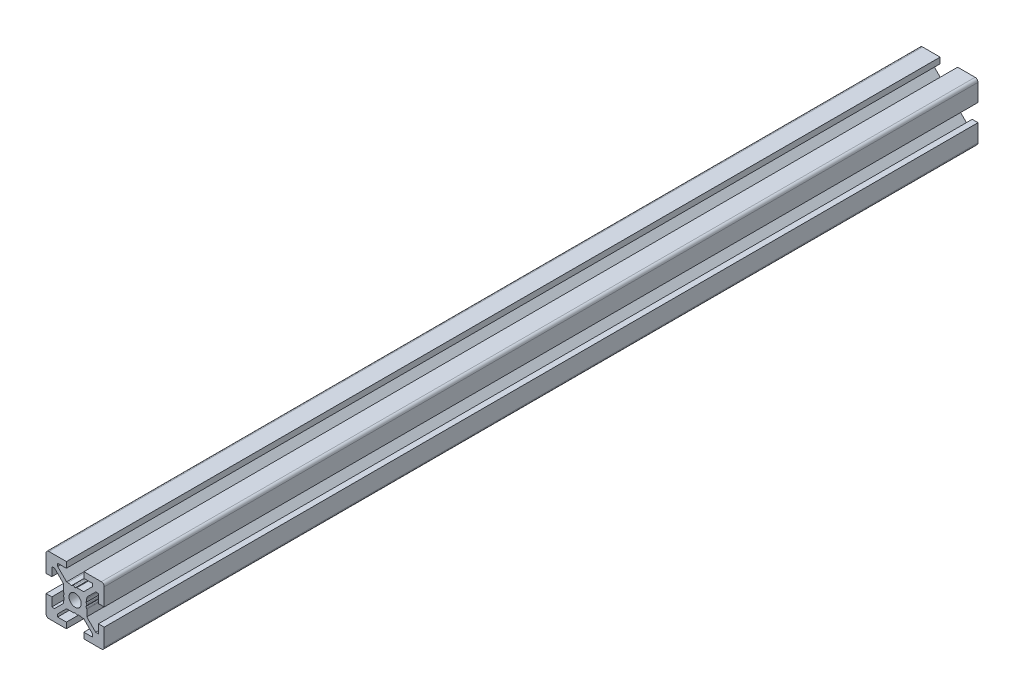
SolidWorks part; units mm, degrees
ref_plane "Front Plane" through (0, 0, 0) normal (0, 0, 1) x (1, 0, 0)
ref_plane "Top Plane" through (0, 0, 0) normal (0, 1, 0) x (1, 0, 0)
ref_plane "Right Plane" through (0, 0, 0) normal (1, 0, 0) x (0, 0, -1)
ref_plane "Plane1" through (0, 0, -2000) normal (0, 0, -1) x (-1, 0, 0)
sketch "Sketch1" plane through (0, 0, -2000) normal (0, 0, -1) x (-1, 0, 0)
  line L0 (10, -3) -> (8, -3)
  line L1 (8, -3) -> (8, -6)
  line L2 (8, -6) -> (7.0607, -6)
  line L3 (7.0607, -6) -> (4, -2.9393)
  line L4 (4, -2.9393) -> (4, -2.5)
  line L5 (4, -2.5) -> (3.751, -1.2189)
  line L6 (3.751, -1.2189) -> (3.933, -0.9036)
  line L7 (3.933, -0.4036) -> (3.7, 0)
  line L8 (3.7, 0) -> (3.933, 0.4036)
  line L9 (4, 0.6536) -> (4, 2.9393)
  line L10 (4, 2.9393) -> (7.0607, 6)
  line L11 (7.0607, 6) -> (8, 6)
  line L12 (8, 6) -> (8, 3)
  line L13 (8, 3) -> (10, 3)
  line L14 (10, 3) -> (10, 9)
  line L15 (9, 10) -> (3, 10)
  line L16 (3, 10) -> (3, 8)
  line L17 (3, 8) -> (6, 8)
  line L18 (6, 8) -> (6, 7.0607)
  line L19 (6, 7.0607) -> (2.9393, 4)
  line L20 (2.9393, 4) -> (2.5, 4)
  line L21 (2.5, 4) -> (1.2189, 3.751)
  line L22 (1.2189, 3.751) -> (0.9036, 3.933)
  line L23 (0.4036, 3.933) -> (0, 3.7)
  line L24 (0, 3.7) -> (-0.4036, 3.933)
  line L25 (-0.6536, 4) -> (-2.9393, 4)
  line L26 (-2.9393, 4) -> (-6, 7.0607)
  line L27 (-6, 7.0607) -> (-6, 8)
  line L28 (-6, 8) -> (-3, 8)
  line L29 (-3, 8) -> (-3, 10)
  line L30 (-3, 10) -> (-9, 10)
  line L31 (-10, 9) -> (-10, 3)
  line L32 (-10, 3) -> (-8, 3)
  line L33 (-8, 3) -> (-8, 6)
  line L34 (-8, 6) -> (-7.0607, 6)
  line L35 (-7.0607, 6) -> (-4, 2.9393)
  line L36 (-4, 2.9393) -> (-4, 2.5)
  line L37 (-4, 2.5) -> (-3.751, 1.2189)
  line L38 (-3.751, 1.2189) -> (-3.933, 0.9036)
  line L39 (-3.933, 0.4036) -> (-3.7, 0)
  line L40 (-3.7, 0) -> (-3.933, -0.4036)
  line L41 (-4, -0.6536) -> (-4, -2.9393)
  line L42 (-4, -2.9393) -> (-7.0607, -6)
  line L43 (-7.0607, -6) -> (-8, -6)
  line L44 (-8, -6) -> (-8, -3)
  line L45 (-8, -3) -> (-10, -3)
  line L46 (-10, -3) -> (-10, -9)
  line L47 (-9, -10) -> (-3, -10)
  line L48 (-3, -10) -> (-3, -8)
  line L49 (-3, -8) -> (-6, -8)
  line L50 (-6, -8) -> (-6, -7.0607)
  line L51 (-6, -7.0607) -> (-2.9393, -4)
  line L52 (-2.9393, -4) -> (-2.5, -4)
  line L53 (-2.5, -4) -> (-1.2189, -3.751)
  line L54 (-1.2189, -3.751) -> (-0.9036, -3.933)
  line L55 (-0.4036, -3.933) -> (0, -3.7)
  line L56 (0, -3.7) -> (0.4036, -3.933)
  line L57 (0.6536, -4) -> (2.9393, -4)
  line L58 (2.9393, -4) -> (6, -7.0607)
  line L59 (6, -7.0607) -> (6, -8)
  line L60 (6, -8) -> (3, -8)
  line L61 (3, -8) -> (3, -10)
  line L62 (3, -10) -> (9, -10)
  line L63 (10, -9) -> (10, -3)
  circle A0 centre (0, 0) radius 2.1
  arc A1 (3.933, -0.9036) -> (3.933, -0.4036) centre (3.5, -0.6536) ccw
  arc A2 (3.933, 0.4036) -> (4, 0.6536) centre (3.5, 0.6536) ccw
  arc A3 (10, 9) -> (9, 10) centre (9, 9) ccw
  arc A4 (0.9036, 3.933) -> (0.4036, 3.933) centre (0.6536, 3.5) ccw
  arc A5 (-0.4036, 3.933) -> (-0.6536, 4) centre (-0.6536, 3.5) ccw
  arc A6 (-9, 10) -> (-10, 9) centre (-9, 9) ccw
  arc A7 (-3.933, 0.9036) -> (-3.933, 0.4036) centre (-3.5, 0.6536) ccw
  arc A8 (-3.933, -0.4036) -> (-4, -0.6536) centre (-3.5, -0.6536) ccw
  arc A9 (-10, -9) -> (-9, -10) centre (-9, -9) ccw
  arc A10 (-0.9036, -3.933) -> (-0.4036, -3.933) centre (-0.6536, -3.5) ccw
  arc A11 (0.4036, -3.933) -> (0.6536, -4) centre (0.6536, -3.5) ccw
  arc A12 (9, -10) -> (10, -9) centre (9, -9) ccw
extrude "Boss-Extrude1" add sketch "Sketch1" against normal blind 300
